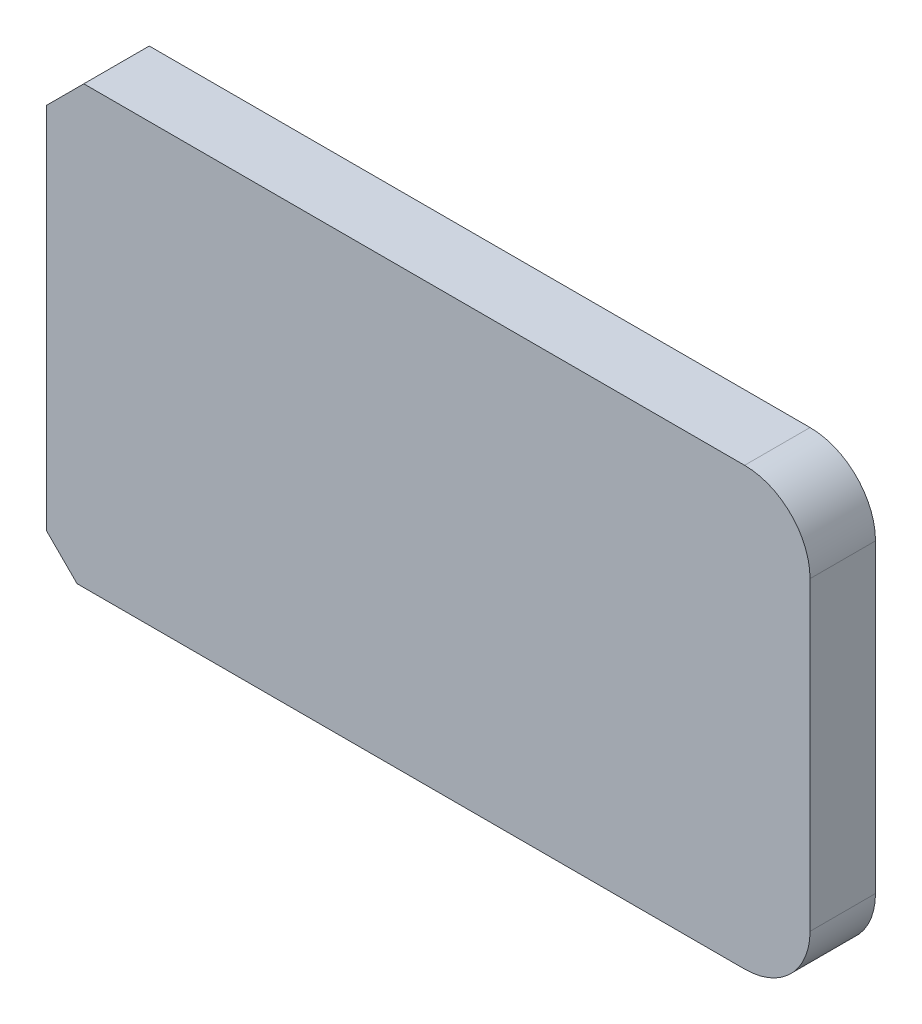
SolidWorks part; units mm, degrees
ref_plane "Front Plane" through (0, 0, 0) normal (0, 0, 1) x (1, 0, 0)
ref_plane "Top Plane" through (0, 0, 0) normal (0, 1, 0) x (1, 0, 0)
ref_plane "Right Plane" through (0, 0, 0) normal (1, 0, 0) x (0, 0, -1)
sketch "Sketch1" plane through (0, 0, 0) normal (0, 0, 1) x (1, 0, 0)
  line L0 (0, 0) -> (0, 44948.7657) construction
  line L1 (-74.5424, 42.5125) -> (-67.7018, 49.3531)
  line L2 (-67.7018, 49.3531) -> (53.4576, 49.3531)
  line L3 (65.4576, 37.3531) -> (65.4576, -18.6469)
  line L4 (53.4576, -30.6469) -> (-68.9371, -30.6469)
  line L5 (-68.9371, -30.6469) -> (-74.5424, -25.0416)
  line L6 (-74.5424, -25.0416) -> (-74.5424, 42.5125)
  arc A0 (65.4576, -18.6469) -> (53.4576, -30.6469) centre (53.4576, -18.6469) cw
  arc A1 (53.4576, 49.3531) -> (65.4576, 37.3531) centre (53.4576, 37.3531) cw
  dimension "D5" = 12
  dimension "D1" = 140
  dimension "D2" = 80
  dimension "D3" = 45
  dimension "D4" = 45
extrude "Boss-Extrude1" add sketch "Sketch1" along normal blind 12
